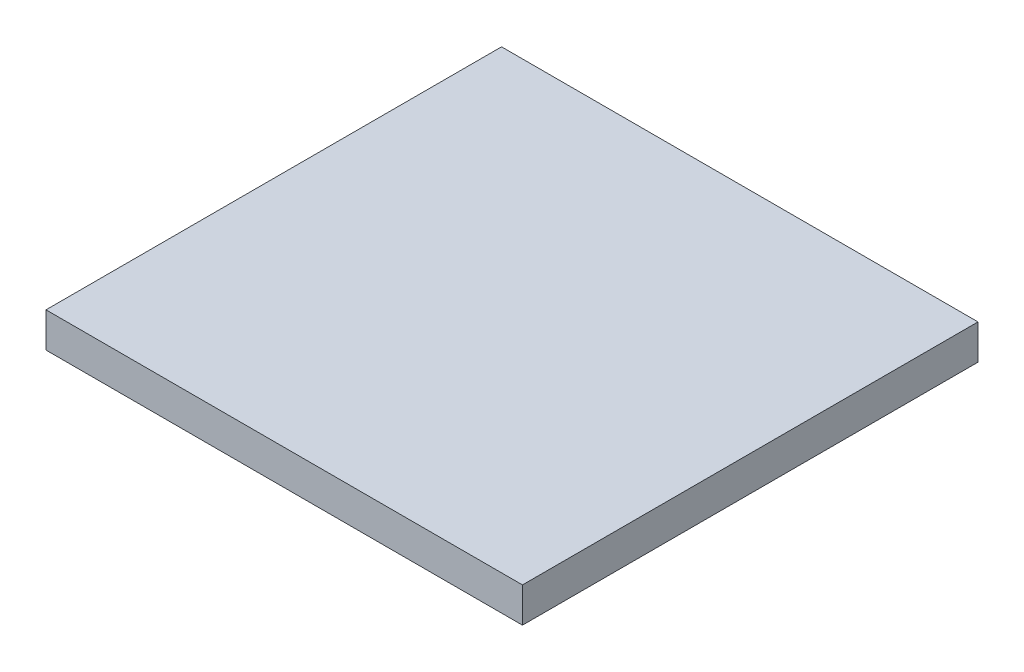
SolidWorks part; units mm, degrees
ref_plane "Alzado" through (0, 0, 0) normal (0, 0, 1) x (1, 0, 0)
ref_plane "Planta" through (0, 0, 0) normal (0, 1, 0) x (1, 0, 0)
ref_plane "Vista lateral" through (0, 0, 0) normal (1, 0, 0) x (0, 0, -1)
sketch "Croquis1" plane through (0, 0, 0) normal (0, 1, 0) x (1, 0, 0)
  line L1 (34.15, 32.65) -> (-34.15, 32.65)
  line L2 (34.15, 32.65) -> (34.15, -32.65)
  line L3 (34.15, -32.65) -> (-34.15, -32.65)
  line L4 (-34.15, 32.65) -> (-34.15, -32.65)
  line L5 (34.15, 32.65) -> (-34.15, -32.65) construction
  line L6 (34.15, -32.65) -> (-34.15, 32.65) construction
  point P0 (0, 0)
  dimension "D1" = 68.3
  dimension "D2" = 65.3
extrude "Saliente-Extruir1" add sketch "Croquis1" along normal blind 5
